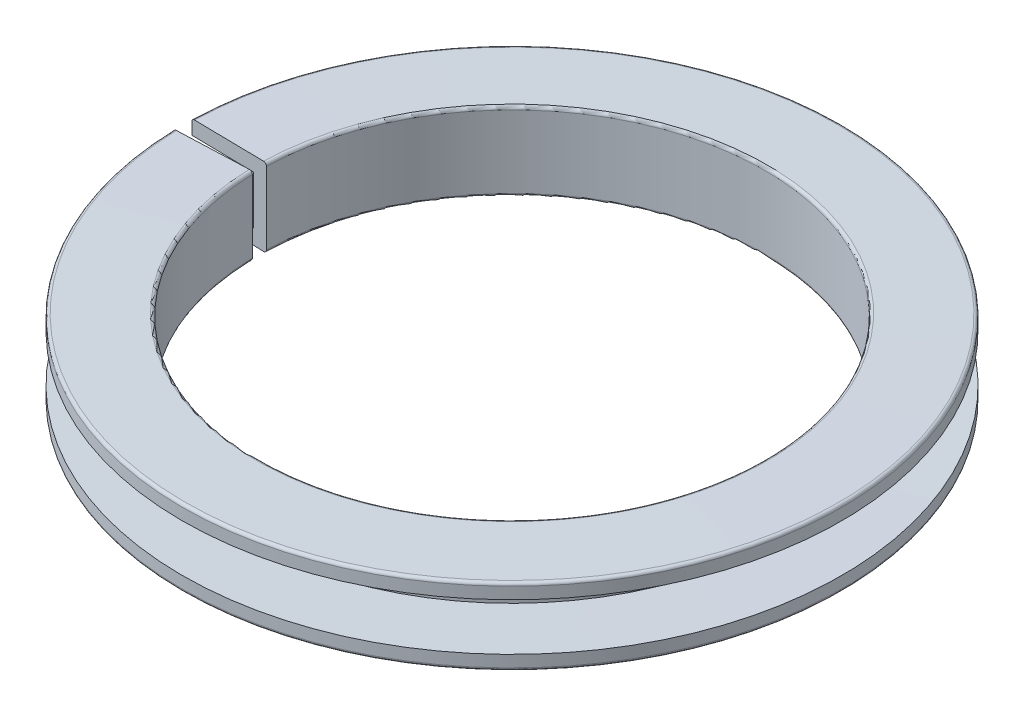
SolidWorks part; units mm, degrees
ref_plane "正面" through (0, 0, 0) normal (0, 0, 1) x (1, 0, 0)
ref_plane "平面" through (0, 0, 0) normal (0, 1, 0) x (1, 0, 0)
ref_plane "右側面" through (0, 0, 0) normal (1, 0, 0) x (0, 0, -1)
sketch "ｽｹｯﾁ1" plane through (0, 0, 0) normal (0, 0, 1) x (1, 0, 0)
  line L0 (4.3, -1.6) -> (4.3, -2.3918)
  line L1 (0, 1.65) -> (4.3, 1.6)
  line L2 (0, 1.65) -> (0, -1.65)
  line L3 (-0.6977, -2.6476) -> (4.1023, -2.5918)
  line L4 (0, 0) -> (4.3, 0) construction
  line L5 (-0.6977, 2.6476) -> (4.1023, 2.5918)
  line L6 (-0.9, 2.4477) -> (-0.9, -2.4477)
  line L7 (0, -1.65) -> (4.3, -1.6)
  line L8 (4.3, 2.3918) -> (4.3, 1.6)
  line L9 (4.3, 1.6) -> (0, 1.6) construction
  arc A0 (4.1023, -2.5918) -> (4.3, -2.3918) centre (4.1, -2.3918) ccw
  arc A1 (-0.9, -2.4477) -> (-0.6977, -2.6476) centre (-0.7, -2.4477) ccw
  arc A2 (-0.6977, 2.6476) -> (-0.9, 2.4477) centre (-0.7, 2.4477) ccw
  arc A3 (4.1023, 2.5918) -> (4.3, 2.3918) centre (4.1, 2.3918) cw
  point P1 (-0.9, 0)
  point P6 (0, 0)
  point P15 (4.3, -2.5895)
  point P19 (-0.9, -2.65)
  point P22 (-0.9, 2.65)
  point P25 (4.3, 2.5895)
  dimension "D6" = 0.2
  dimension "D1" = 3.3
  dimension "D2" = 5.3
  dimension "D3" = 0.9
  dimension "D4" = 3.2
  dimension "D5" = 5.2
sketch "ｽｹｯﾁ2" plane through (0, 0, 0) normal (0, 1, 0) x (1, 0, 0)
  line L0 (-18, 0) -> (-36, 0) construction
  line L1 (-18, 0.5) -> (-36, 0.5) construction
  line L2 (-18, -0.5) -> (-36, -0.5) construction
  arc A0 (-35.9931, -0.5) -> (-35.9931, 0.5) centre (-18, 0) ccw
  point P2 (0, 0)
  dimension "D1" = 36
  dimension "D2" = 0.5
  dimension "D3" = 0.5
sweep "ｽｲｰﾌﾟ1" add profiles "ｽｹｯﾁ1" path "ｽｹｯﾁ2"
